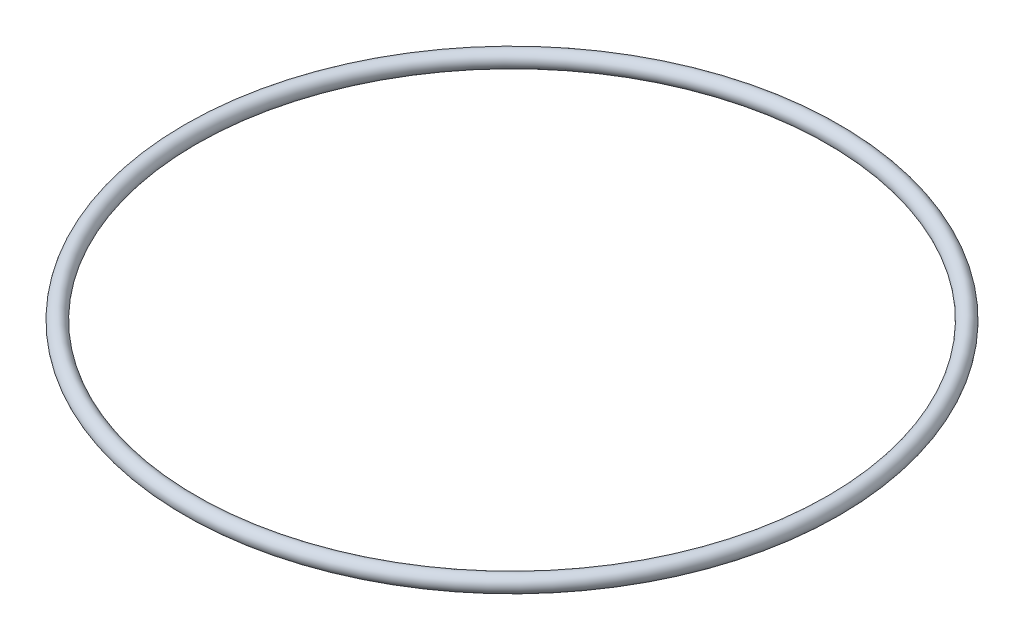
SolidWorks part; units mm, degrees
material "Silicon Rubber"
ref_plane "Front Plane" through (0, 0, 0) normal (0, 0, 1) x (1, 0, 0)
ref_plane "Top Plane" through (0, 0, 0) normal (0, 1, 0) x (1, 0, 0)
ref_plane "Right Plane" through (0, 0, 0) normal (1, 0, 0) x (0, 0, -1)
sketch "Sketch6" plane through (0, 0, 0) normal (0, 1, 0) x (1, 0, 0)
  circle A1 centre (0, 0) radius 35.6743
sketch "Sketch9" plane through (0, 0, 0) normal (0, 0, 1) x (1, 0, 0)
  line L1 (35.6743, 0) -> (-35.6743, 0) construction
  circle A0 centre (-35.6743, 0) radius 0.889
sweep "Sweep5" add profiles "Sketch9" path "Sketch6"
